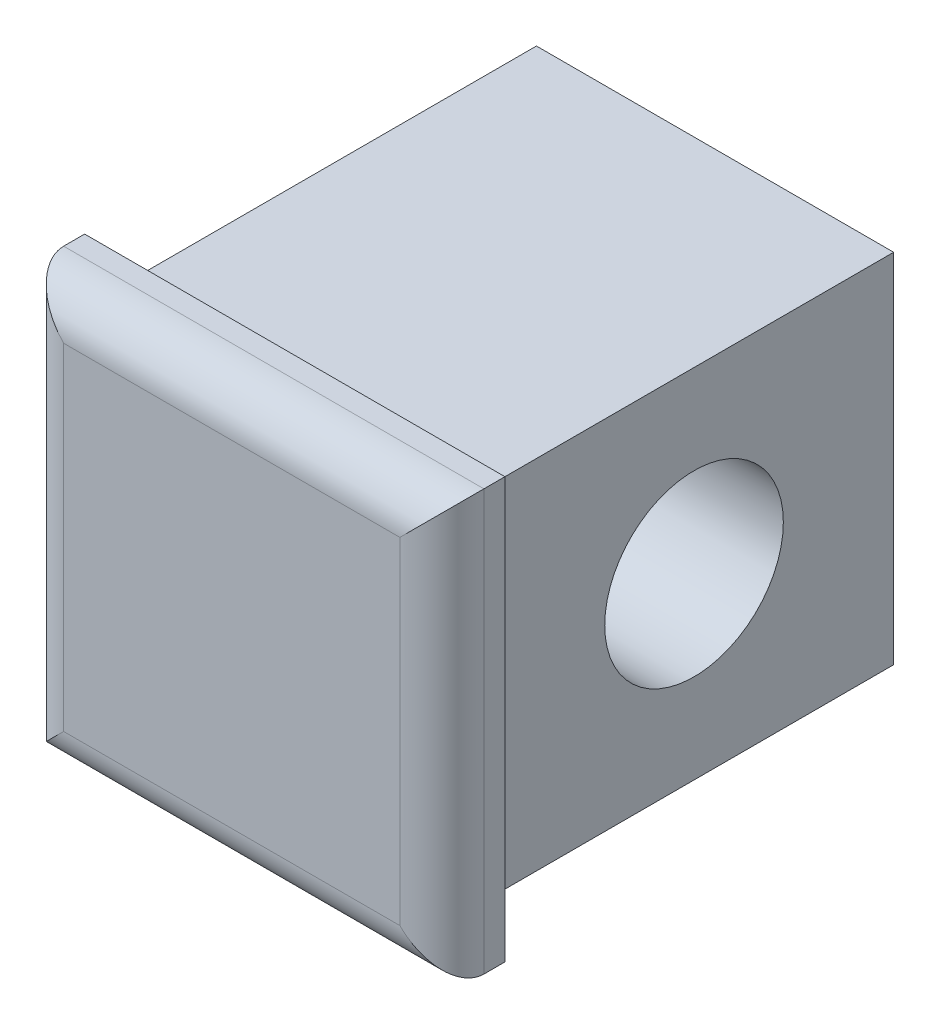
SolidWorks part; units mm, degrees
ref_plane "Front Plane" through (0, 0, 0) normal (0, 0, 1) x (1, 0, 0)
ref_plane "Top Plane" through (0, 0, 0) normal (0, 1, 0) x (1, 0, 0)
ref_plane "Right Plane" through (0, 0, 0) normal (1, 0, 0) x (0, 0, -1)
sketch "Sketch1" plane through (0, 0, 0) normal (1, 0, 0) x (0, 0, -1)
  line L0 (0, 10) -> (0, -10)
  line L1 (0, 10) -> (-3, 10)
  line L2 (-3, 10) -> (-3, -10)
  line L3 (-3, -10) -> (0, -10)
  point P1 (0, 0)
  point P6 (0, 0)
  point P8 (0, 0)
  point P9 (0, 0)
  dimension "D1" = 3
  dimension "D2" = 20
extrude "Boss-Extrude1" add sketch "Sketch1" along normal mid plane 20
sketch "Sketch2" plane through (0, 0, 0) normal (0, 0, -1) x (-1, 0, 0)
  line L1 (-8.5, -8.5) -> (8.5, -8.5)
  line L2 (-8.5, -8.5) -> (-8.5, 8.5)
  line L3 (-8.5, 8.5) -> (8.5, 8.5)
  line L4 (8.5, -8.5) -> (8.5, 8.5)
  line L5 (-8.5, -8.5) -> (8.5, 8.5) construction
  line L6 (-8.5, 8.5) -> (8.5, -8.5) construction
  point P0 (0, 0)
  dimension "D1" = 17
extrude "Boss-Extrude2" add sketch "Sketch2" along normal blind 20
sketch "Sketch3" plane through (8.5, 0, 0) normal (1, 0, 0) x (0, 0, -1)
  line L0 (0, 0) -> (10.5, 0) construction
  line L1 (0, -10) -> (0, 10) construction
  circle A0 centre (10.5, 0) radius 4.25
  point P3 (0, 0)
  dimension "D2" = 8.5
  dimension "D1" = 10.5
extrude "Cut-Extrude1" cut sketch "Sketch3" against normal through all
fillet "Fillet1" radius 2 4 edges at (0, 10, 3) (10, 0, 3) (0, -10, 3) (-10, 0, 3)
